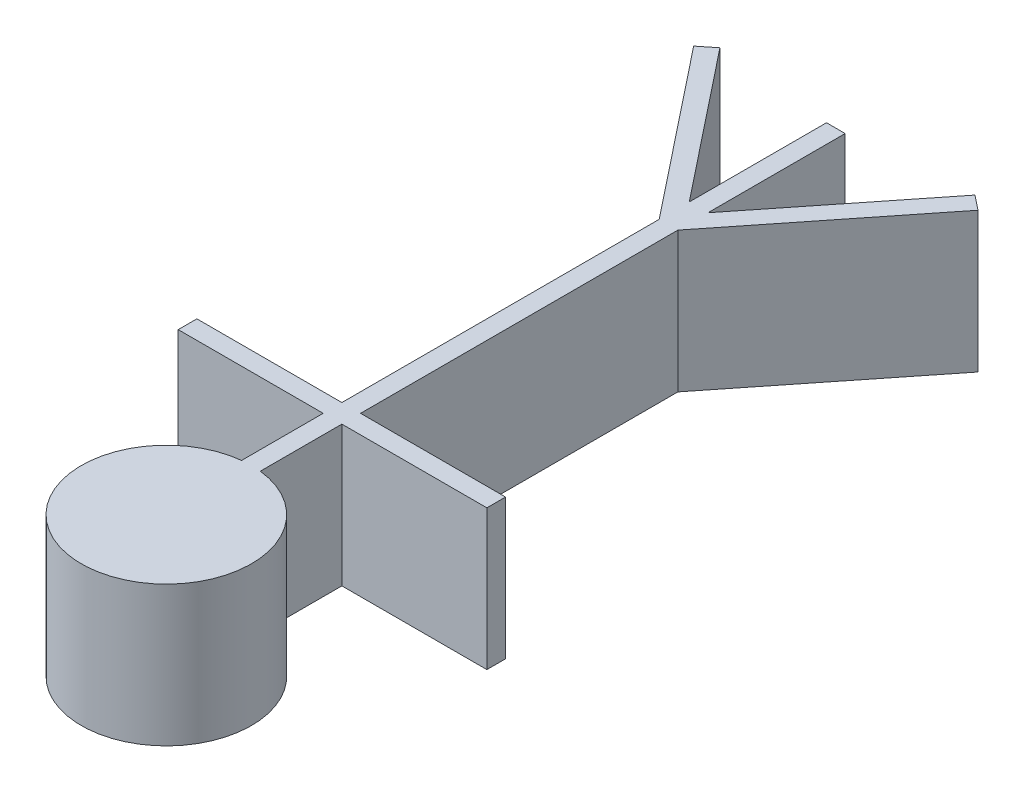
SolidWorks part; units mm, degrees
ref_plane "Front Plane" through (0, 0, 0) normal (0, 0, 1) x (1, 0, 0)
ref_plane "Top Plane" through (0, 0, 0) normal (0, 1, 0) x (1, 0, 0)
ref_plane "Right Plane" through (0, 0, 0) normal (1, 0, 0) x (0, 0, -1)
sketch "Sketch1" plane through (0, 0, 0) normal (0, 1, 0) x (1, 0, 0)
  line L0 (2, -107.7495) -> (33.0386, -107.7495)
  line L1 (-33.0386, -107.7495) -> (-2, -107.7495)
  line L2 (2, -35.812) -> (30.4354, 0)
  line L3 (-2, -35.812) -> (-30.4354, 0)
  line L4 (-33.0386, -107.7495) -> (33.0386, -107.7495) construction
  line L5 (-33.0386, -103.7495) -> (-2, -103.7495)
  line L6 (-2, -29.3794) -> (-27.3028, 2.4873)
  line L7 (2, -29.3794) -> (27.3028, 2.4873)
  line L8 (-2, 0) -> (-2, -29.3794)
  line L9 (-2, -107.7495) -> (-2, -125.2142)
  line L10 (2, 0) -> (2, -29.3794)
  line L11 (2, -107.7495) -> (2, -125.2142)
  line L12 (2, -103.7495) -> (33.0386, -103.7495)
  line L13 (-33.0386, -103.7495) -> (33.0386, -103.7495) construction
  line L14 (-33.0386, -107.7495) -> (-33.0386, -103.7495)
  line L15 (33.0386, -107.7495) -> (33.0386, -103.7495)
  line L16 (-30.4354, 0) -> (-27.3028, 2.4873)
  line L17 (-2, 0) -> (2, 0)
  line L18 (27.3028, 2.4873) -> (30.4354, 0)
  line L19 (2, -35.812) -> (2, -103.7495)
  line L23 (-2, -35.812) -> (-2, -103.7495)
  line L25 (0, -31.8982) -> (-27.3028, 2.4873) construction
  line L26 (0, -31.8982) -> (27.3028, 2.4873) construction
  line L27 (0, -38.3308) -> (30.4354, 0) construction
  line L28 (0, -38.3308) -> (-30.4354, 0) construction
  arc A0 (-2, -125.2142) -> (2, -125.2142) centre (0, -143.3266) ccw
  dimension "D1" = 4
extrude "Boss-Extrude1" add sketch "Sketch1" along normal blind 30
